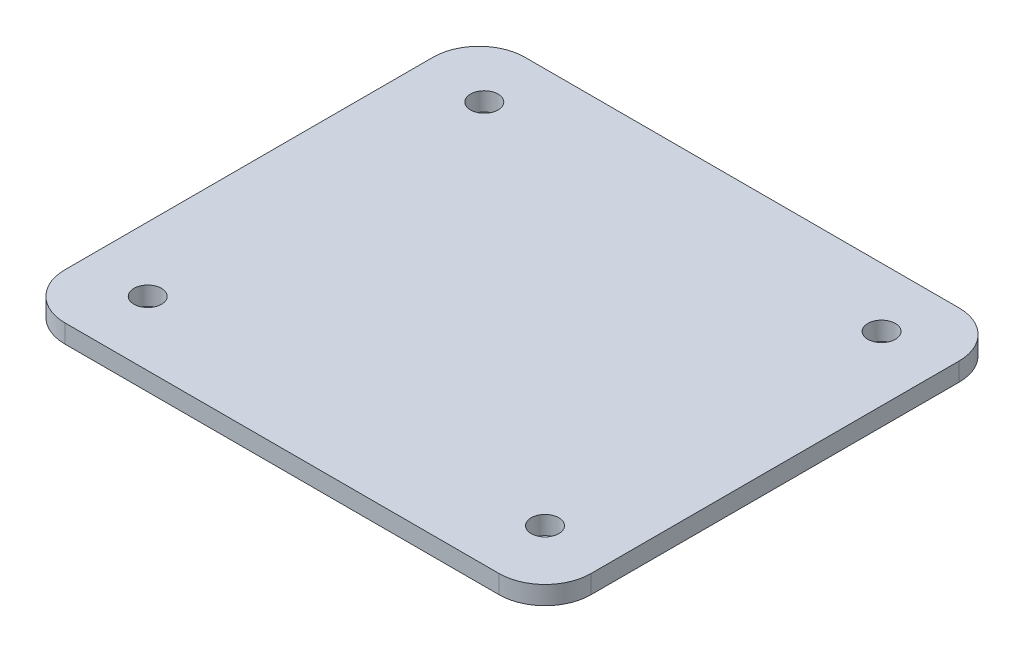
SolidWorks part; units mm, degrees
material "ABS"
ref_plane "Front Plane" through (0, 0, 0) normal (0, 0, 1) x (1, 0, 0)
ref_plane "Top Plane" through (0, 0, 0) normal (0, 1, 0) x (1, 0, 0)
ref_plane "Right Plane" through (0, 0, 0) normal (1, 0, 0) x (0, 0, -1)
sketch "Sketch1" plane through (0, 0, 0) normal (0, 1, 0) x (1, 0, 0)
  line L1 (0, 0) -> (57.18, 0)
  line L2 (0, 0) -> (0, -50)
  line L3 (0, -50) -> (57.18, -50)
  line L4 (57.18, 0) -> (57.18, -50)
  circle A0 centre (7, -6.42) radius 1.5
  circle A1 centre (50.18, -6.42) radius 1.5
  circle A2 centre (50.18, -43) radius 1.5
  circle A3 centre (7, -43) radius 1.5
  dimension "D3" = 3
  dimension "D4" = 3
  dimension "D5" = 3
  dimension "D6" = 3
  dimension "D2" = 50
  dimension "D7" = 43.18
  dimension "D8" = 36.58
  dimension "D9" = 7
  dimension "D10" = 7
  dimension "D11" = 7
extrude "Boss-Extrude1" add sketch "Sketch1" along normal blind 2
fillet "Fillet2" radius 5 4 edges at (57.18, 1, 0) (0, 1, 0) (57.18, 1, 50) (0, 1, 50)
